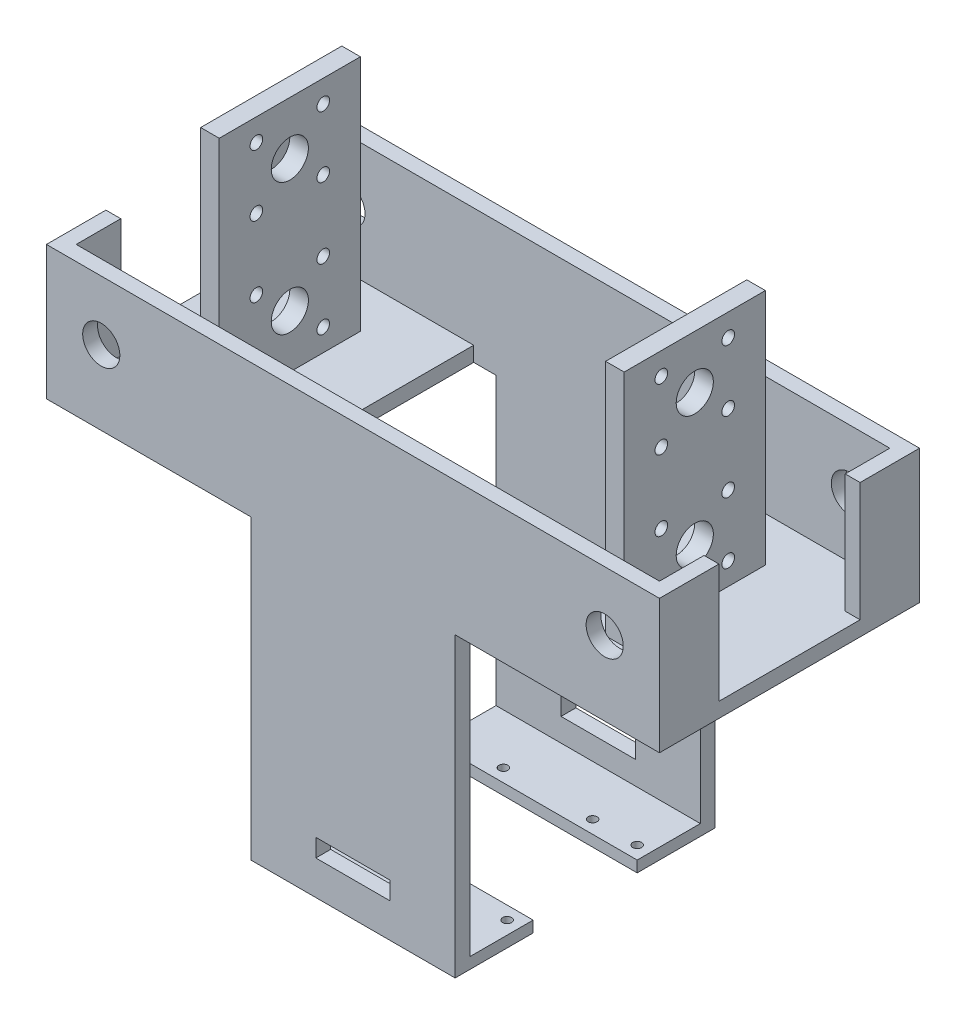
SolidWorks part; units mm, degrees
ref_plane "Front Plane" through (0, 0, 0) normal (0, 0, 1) x (1, 0, 0)
ref_plane "Top Plane" through (0, 0, 0) normal (0, 1, 0) x (1, 0, 0)
ref_plane "Right Plane" through (0, 0, 0) normal (1, 0, 0) x (0, 0, -1)
sketch "Sketch1" plane through (0, 0, 0) normal (0, 1, 0) x (1, 0, 0)
  line L0 (0, 0) -> (0, -14.43) construction
  line L1 (-37.5, 20) -> (37.5, 20)
  line L2 (-37.5, 20) -> (-37.5, -20)
  line L3 (-37.5, -20) -> (37.5, -20)
  line L4 (37.5, 20) -> (37.5, -20)
  line L5 (-37.5, 20) -> (37.5, -20) construction
  line L6 (-37.5, -20) -> (37.5, 20) construction
  line L7 (0, 0) -> (6.508, 0) construction
  line L8 (-5, 10) -> (5, 10)
  line L9 (-5, 10) -> (-5, -10)
  line L10 (-5, -10) -> (5, -10)
  line L11 (5, 10) -> (5, -10)
  line L12 (-5, 10) -> (5, -10) construction
  line L13 (-5, -10) -> (5, 10) construction
  circle A0 centre (-21, 0) radius 5
  circle A1 centre (-30, 8.25) radius 1.7
  circle A2 centre (-12, 8.25) radius 1.7
  circle A3 centre (-12, -8.25) radius 1.7
  circle A4 centre (-30, -8.25) radius 1.7
  circle A5 centre (12, 8.25) radius 1.7
  circle A6 centre (12, -8.25) radius 1.7
  circle A7 centre (21, 0) radius 5
  circle A8 centre (30, -8.25) radius 1.7
  circle A9 centre (30, 8.25) radius 1.7
  point P0 (0, 0)
  dimension "D3" = 10
  dimension "D4" = 16.5
  dimension "D5" = 16.5
  dimension "D6" = 18
  dimension "D9" = 10
  dimension "D11" = 20
  dimension "D13" = 7.5
  dimension "D17" = 3.4
  dimension "D19" = 11.75
  dimension "D20" = 11.75
  dimension "D1" = 75
  dimension "D2" = 40
  dimension "D10" = 10
  dimension "D7" = 2
  dimension "D8" = 2
extrude "Boss-Extrude1" add sketch "Sketch1" along normal blind 3
sketch "Sketch2" plane through (0, 3, 0) normal (0, 1, 0) x (1, 0, 0)
  line L0 (-37.5, 20) -> (-37.5, -20) construction
  line L1 (-33.5, 14) -> (33.5, 14)
  line L2 (-33.5, 14) -> (-33.5, -14)
  line L3 (-33.5, -14) -> (33.5, -14)
  line L4 (33.5, 14) -> (33.5, -14)
  line L5 (37.5, -20) -> (37.5, 20) construction
  line L6 (37.5, 20) -> (-37.5, 20) construction
  line L7 (-37.5, -20) -> (37.5, -20) construction
  dimension "D1" = 4
  dimension "D2" = 4
  dimension "D3" = 6
  dimension "D4" = 6
extrude "Cut-Extrude1" cut sketch "Sketch2" against normal through all both and the other way through all
sketch "Sketch3" plane through (0, 3, 0) normal (0, 1, 0) x (1, 0, 0)
  line L1 (37.5, 20) -> (-37.5, 20)
  line L2 (37.5, 20) -> (37.5, 35)
  line L3 (37.5, 35) -> (-37.5, 35)
  line L4 (-37.5, 20) -> (-37.5, 35)
  line L5 (-37.5, -20) -> (37.5, -20)
  line L6 (-37.5, -20) -> (-37.5, -35)
  line L7 (-37.5, -35) -> (37.5, -35)
  line L8 (37.5, -20) -> (37.5, -35)
  line L10 (-37.5, 20) -> (-33.5, 20)
  line L11 (-37.5, 20) -> (-37.5, -20)
  line L12 (-37.5, -20) -> (-33.5, -20)
  line L13 (-33.5, 20) -> (-33.5, -20)
  line L14 (37.5, 20) -> (33.5, 20)
  line L15 (37.5, 20) -> (37.5, -20)
  line L16 (37.5, -20) -> (33.5, -20)
  line L17 (33.5, 20) -> (33.5, -20)
  line M3 (-33.5, -14) -> (-33.5, 14)
  line M5 (33.5, 14) -> (33.5, -14)
  line M11 (37.5, -20) -> (37.5, 20)
  line M12 (37.5, 20) -> (-37.5, 20)
  line M13 (-37.5, 20) -> (-37.5, -20)
  line M14 (-37.5, -20) -> (37.5, -20)
  dimension "D1" = 15
  dimension "D2" = 15
extrude "Boss-Extrude3" add sketch "Sketch3" along normal blind 110 and the other way blind 3 contours L8 L5 L6 L7 M14 | L4 L1 L2 L3 M12 | L17 M12 M5 M14 M11 | L13 L1 M13 M14 M3
sketch "Sketch6" plane through (0, 3, 0) normal (0, 1, 0) x (1, 0, 0)
  line L0 (-37.5, -35) -> (37.5, -35) construction
  line L1 (-33.5, -20) -> (33.5, -20)
  line L2 (-33.5, -20) -> (-33.5, -31)
  line L3 (-33.5, -31) -> (33.5, -31)
  line L4 (33.5, -20) -> (33.5, -31)
  line L5 (33.5, 20) -> (-33.5, 20)
  line L6 (33.5, 20) -> (33.5, 31)
  line L7 (33.5, 31) -> (-33.5, 31)
  line L8 (-33.5, 20) -> (-33.5, 31)
  line L9 (37.5, 35) -> (-37.5, 35) construction
  dimension "D1" = 4
  dimension "D2" = 4
extrude "Cut-Extrude4" cut sketch "Sketch6" along normal through all
sketch "Sketch7" plane through (-37.5, 0, 0) normal (-1, 0, 0) x (0, 0, 1)
  line L0 (35, 0) -> (35, 113) construction
  line L1 (-35, 113) -> (35, 113)
  line L2 (-35, 113) -> (-35, 76)
  line L3 (-35, 76) -> (35, 76)
  line L4 (35, 113) -> (35, 76)
  dimension "D1" = 37
extrude "Boss-Extrude4" add sketch "Sketch7" along normal blind 45
ref_plane "Plane1" through (0, 0, 0) normal (1, 0, 0) x (0, 0, -1)
mirror "Mirror2" about plane through (0, 0, 0) normal (1, 0, 0) of "Boss-Extrude4"
sketch "Sketch8" plane through (0, 113, 0) normal (0, 1, 0) x (1, 0, 0)
  line L0 (-82.5, -35) -> (-82.5, 35) construction
  line L1 (-33.5, 31) -> (-78.5, 31)
  line L2 (-33.5, 31) -> (-33.5, -31)
  line L3 (-33.5, -31) -> (-78.5, -31)
  line L4 (-78.5, 31) -> (-78.5, -31)
  line L5 (33.5, -31) -> (78.5, -31)
  line L6 (33.5, -31) -> (33.5, 31)
  line L7 (33.5, 31) -> (78.5, 31)
  line L8 (78.5, -31) -> (78.5, 31)
  line L9 (82.5, -35) -> (82.5, 35) construction
  dimension "D1" = 4
  dimension "D2" = 4
extrude "Cut-Extrude6" cut sketch "Sketch8" against normal blind 29
sketch "Sketch9" plane through (-82.5, 0, 0) normal (-1, 0, 0) x (0, 0, 1)
  line L18 (-31, 84) -> (31, 84) construction
  line L19 (-19, 84) -> (19, 84)
  line L20 (-19, 84) -> (-19, 112.5)
  line L21 (-19, 112.5) -> (19, 112.5)
  line L22 (19, 84) -> (19, 112.5)
  line L25 (-31, 84) -> (-31, 113) construction
  dimension "D1" = 38
  dimension "D2" = 12
  dimension "D3" = 28.5
sketch "Sketch11" plane through (0, 0, 35) normal (0, 0, 1) x (1, 0, 0)
  line L0 (82.5, 76) -> (82.5, 113) construction
  line L1 (-82.5, 76) -> (-37.5, 76)
  line L2 (-82.5, 76) -> (-82.5, 80)
  line L3 (-82.5, 80) -> (-37.5, 80)
  line L4 (-37.5, 76) -> (-37.5, 80)
  line L5 (37.5, 76) -> (82.5, 76)
  line L6 (37.5, 76) -> (37.5, 80)
  line L7 (37.5, 80) -> (82.5, 80)
  line L8 (82.5, 76) -> (82.5, 80)
  line L11 (-78.5, 84) -> (-33.5, 84) construction
  line L12 (33.5, 84) -> (78.5, 84) construction
  dimension "D1" = 4
  dimension "D2" = 4
extrude "Cut-Extrude9" cut sketch "Sketch11" against normal through all
extrude "Cut-Extrude10" cut sketch "Sketch9" against normal through all
sketch "Sketch13" plane through (0, 84, 0) normal (0, 1, 0) x (1, 0, 0)
  line L0 (-78.5, 31) -> (-78.5, -31) construction
  line L1 (-57, 19) -> (-52, 19)
  line L2 (-57, 19) -> (-57, -19)
  line L3 (-57, -19) -> (-52, -19)
  line L4 (-52, 19) -> (-52, -19)
  line L7 (78.5, 31) -> (-78.5, 31) construction
  line L13 (-57, -19) -> (-57, 19)
  line L17 (-82.5, -19) -> (-107.5, -19)
  line L18 (-82.5, -19) -> (-82.5, 19)
  line L19 (-82.5, 19) -> (-107.5, 19)
  line L20 (-107.5, -19) -> (-107.5, 19)
  line L21 (-107.5, 19) -> (-61, 19)
  line L22 (-107.5, 19) -> (-107.5, -19)
  line L23 (-107.5, -19) -> (-61, -19)
  line L24 (-61, 19) -> (-61, -19)
  dimension "D1" = 21.5
  dimension "D2" = 5
  dimension "D3" = 38
  dimension "D4" = 12
  dimension "D5" = 25
  dimension "D6" = 46.5
extrude "Boss-Extrude5" add sketch "Sketch13" along normal blind 32 contours L4 L1 L2 L3
sketch "Sketch14" plane through (-57, 0, 0) normal (-1, 0, 0) x (0, 0, 1)
  line L0 (-19, 116) -> (-19, 84) construction
  line L4 (19, 112.5) -> (-19, 112.5) construction
  circle A0 centre (0, 98.25) radius 5
  circle A1 centre (-9, 106.5) radius 1.7
  circle A2 centre (9, 106.5) radius 1.7
  circle A3 centre (9, 90) radius 1.7
  circle A4 centre (-9, 90) radius 1.7
  dimension "D1" = 19
  dimension "D2" = 9
  dimension "D3" = 10
  dimension "D6" = 3.4
  dimension "D7" = 14.25
  dimension "D8" = 16.5
  dimension "D9" = 18
  dimension "D10" = 8.25
  dimension "D4" = 2
  dimension "D5" = 2
extrude "Cut-Extrude11" cut sketch "Sketch14" against normal blind 32
mirror "Mirror4" about plane through (0, 0, 0) normal (1, 0, 0) of "Boss-Extrude5", "Cut-Extrude11"
sketch "Sketch15" plane through (0, 113, 0) normal (0, 1, 0) x (1, 0, 0)
  line L1 (-82.5, 35) -> (82.5, 35)
  line L2 (-82.5, 35) -> (-82.5, -35)
  line L3 (-82.5, -35) -> (82.5, -35)
  line L4 (82.5, 35) -> (82.5, -35)
  line L5 (-78.5, 31) -> (78.5, 31)
  line L6 (-78.5, 31) -> (-78.5, -31)
  line L7 (-78.5, -31) -> (78.5, -31)
  line L8 (78.5, 31) -> (78.5, -31)
extrude "Boss-Extrude6" add sketch "Sketch15" along normal blind 3
sketch "Sketch16" plane through (0, 0, 35) normal (0, 0, 1) x (1, 0, 0)
  line L1 (-10, 14.0464) -> (10, 14.0464)
  line L2 (-10, 14.0464) -> (-10, 9.2258)
  line L3 (-10, 9.2258) -> (10, 9.2258)
  line L4 (10, 14.0464) -> (10, 9.2258)
  line L5 (-37.5, 0) -> (-37.5, 80) construction
  dimension "D1" = 20
  dimension "D2" = 27.5
extrude "Cut-Extrude12" cut sketch "Sketch16" against normal through all
sketch "Sketch18" plane through (0, 0, 35) normal (0, 0, 1) x (1, 0, 0)
  line L0 (57, 116) -> (57, 84) construction
  line L2 (33.5, 84) -> (78.5, 84) construction
  circle A0 centre (67.75, 100) radius 5
  dimension "D1" = 10.75
  dimension "D2" = 16
  dimension "D3" = 10
extrude "Cut-Extrude14" cut sketch "Sketch18" against normal through all
mirror "Mirror5" about plane through (0, 0, 0) normal (1, 0, 0) of "Cut-Extrude14"
mirror "Mirror6" about plane through (0, 116, 0) normal (0, 1, 0) of "Mirror4", "Boss-Extrude5", "Cut-Extrude11"
sketch "Sketch19" plane through (82.5, 0, 0) normal (1, 0, 0) x (0, 0, -1)
  line L0 (19, 148) -> (19, 84) construction
  line L1 (-19, 112.5) -> (19, 112.5)
  line L2 (-19, 112.5) -> (-19, 116)
  line L3 (-19, 116) -> (19, 116)
  line L4 (19, 112.5) -> (19, 116)
extrude "Cut-Extrude15" cut sketch "Sketch19" against normal blind 10
mirror "Mirror7" about plane through (0, 0, 0) normal (1, 0, 0) of "Cut-Extrude15"
sketch "Sketch20" plane through (0, 3, 0) normal (0, 1, 0) x (1, 0, 0)
  line L0 (33.5, 31) -> (-33.5, 31) construction
  line L1 (-5, -10) -> (5, -10)
  line L2 (-5, -10) -> (-5, 10)
  line L3 (-5, 10) -> (5, 10)
  line L4 (5, -10) -> (5, 10)
  line L5 (-5, -10) -> (5, 10) construction
  line L6 (-5, 10) -> (5, -10) construction
  line L7 (0, 0) -> (0, 17.5) construction
  line L8 (-37.5, 20) -> (37.5, 20)
  line L9 (-37.5, 20) -> (-37.5, -20)
  line L10 (-37.5, -20) -> (37.5, -20)
  line L11 (37.5, 20) -> (37.5, -20)
  line L12 (-37.5, 20) -> (37.5, -20) construction
  line L13 (-37.5, -20) -> (37.5, 20) construction
  line L14 (0, -34.1) -> (0, 34.1) construction
  circle A1 centre (-12, 17.5) radius 1.2
  circle A2 centre (-12, -17.5) radius 1.2
  circle A3 centre (-24, -17.5) radius 1.2
  circle A4 centre (-24, 17.5) radius 1.2
  circle A5 centre (12, -17.5) radius 1.2
  circle A6 centre (24, -17.5) radius 1.2
  circle A7 centre (12, 17.5) radius 1.2
  circle A8 centre (24, 17.5) radius 1.2
  point P2 (0, 0)
  point P10 (0, 0)
  point P33 (0, 0)
  dimension "D1" = 7
  dimension "D2" = 10
  dimension "D4" = 2.5
  dimension "D7" = 35
  dimension "D8" = 7
  dimension "D9" = 2.4
  dimension "D11" = 12
  dimension "D3" = 21
  dimension "D5" = 75
  dimension "D6" = 40
  dimension "D10" = 2
extrude "Cut-Extrude16" cut sketch "Sketch20" against normal blind 10 contours A4 | A1 | A7 | A3 | A2 | A8 | A5 | A6
sketch "Sketch21" plane through (0, 0, 35) normal (0, 0, 1) x (1, 0, 0)
  line L0 (0, -34.1) -> (0, 34.1) construction
  line L1 (37.5, 0) -> (27.5, 0)
  line L2 (37.5, 0) -> (37.5, 80)
  line L3 (37.5, 80) -> (27.5, 80)
  line L4 (27.5, 0) -> (27.5, 80)
  line L5 (-27.5, 0) -> (-27.5, 80)
  line L6 (-37.5, 80) -> (-27.5, 80)
  line L7 (-37.5, 0) -> (-37.5, 80)
  line L8 (-37.5, 0) -> (-27.5, 0)
  dimension "D1" = 10
  dimension "D2" = 80
extrude "Cut-Extrude17" cut sketch "Sketch21" against normal through all
